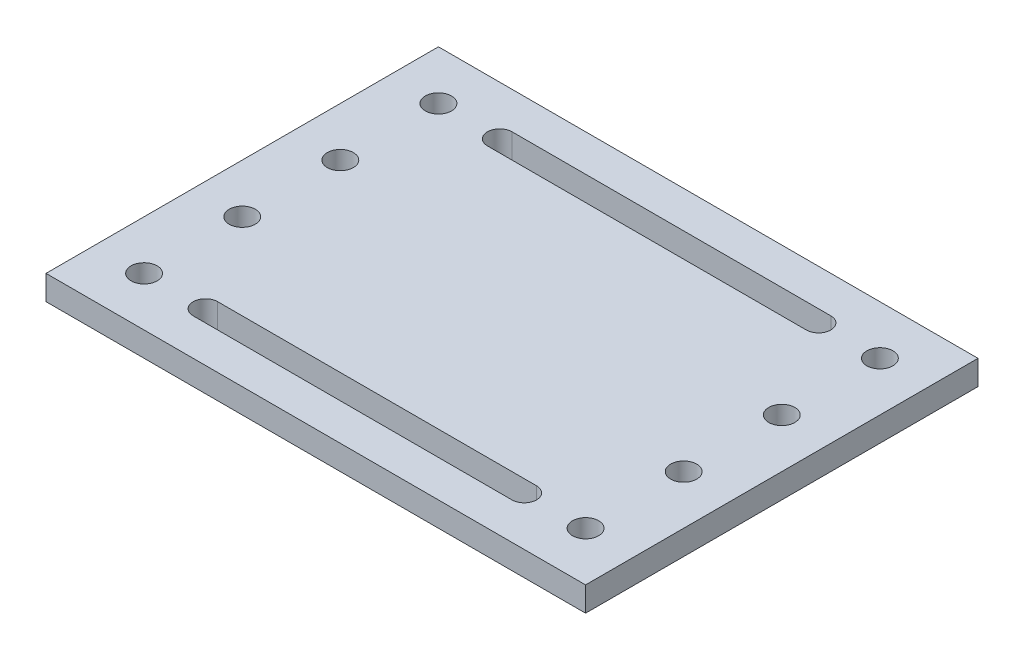
SolidWorks part; units mm, degrees
ref_plane "Front Plane" through (0, 0, 0) normal (0, 0, 1) x (1, 0, 0)
ref_plane "Top Plane" through (0, 0, 0) normal (0, 1, 0) x (1, 0, 0)
ref_plane "Right Plane" through (0, 0, 0) normal (1, 0, 0) x (0, 0, -1)
sketch "Sketch1" plane through (0, 0, 0) normal (0, 1, 0) x (1, 0, 0)
  line L1 (-228.6, -50.8) -> (228.6, -50.8)
  line L2 (-228.6, -50.8) -> (-228.6, 50.8)
  line L3 (-228.6, 50.8) -> (228.6, 50.8)
  line L4 (228.6, -50.8) -> (228.6, 50.8)
  line L5 (-228.6, -50.8) -> (228.6, 50.8) construction
  line L6 (-228.6, 50.8) -> (228.6, -50.8) construction
  point P0 (0, 0)
  dimension "D1" = 457.2
  dimension "D2" = 101.6
extrude "Boss-Extrude1" add sketch "Sketch1" along normal blind 6.35
sketch "Sketch2" plane through (0, 6.35, 0) normal (0, 1, 0) x (1, 0, 0)
  line L0 (200.025, -38.1) -> (117.475, -38.1) construction
  line L1 (200.025, -41.275) -> (117.475, -41.275)
  line L2 (200.025, -34.925) -> (117.475, -34.925)
  line L3 (228.6, -50.8) -> (228.6, 50.8) construction
  line L6 (-228.6, -50.8) -> (228.6, -50.8) construction
  arc A0 (200.025, -41.275) -> (200.025, -34.925) centre (200.025, -38.1) ccw
  arc A1 (117.475, -34.925) -> (117.475, -41.275) centre (117.475, -38.1) ccw
  point P2 (158.75, -38.1)
  dimension "D1" = 82.55
  dimension "D2" = 28.575
  dimension "D3" = 12.7
  dimension "D4" = 6.35
extrude "Cut-Extrude1" cut sketch "Sketch2" against normal through all
mirror "Mirror1" about plane through (0, 0, 0) normal (0, 0, 1) of "Cut-Extrude1"
mirror "Mirror2" [suppressed] about plane through (0, 0, 0) normal (1, 0, 0)
sketch "Sketch3" plane through (0, 6.35, 0) normal (0, 1, 0) x (1, 0, 0)
  line L1 (228.6, 50.8) -> (-228.6, 50.8) construction
  line L2 (-228.6, 50.8) -> (-228.6, -50.8) construction
  point P0 (-215.9, 12.7)
  point P1 (-215.9, 38.1)
  dimension "D1" = 25.4
  dimension "D2" = 12.7
  dimension "D3" = 12.7
hole_wizard "1/4 Clearance Hole1" positions "Sketch4" profile "Sketch5" hole size "1/4" standard "ANSI Inch" end condition through all
sketch "Sketch4" plane through (0, 6.35, 0) normal (0, 1, 0) x (1, 0, 0)
  point P0 (-215.9, 12.7)
  point P3 (-215.9, 38.1)
sketch "Sketch5" plane through (-215.9, 6.35, -12.7) normal (1, 0, 0) x (0, 0, 1)
  line L0 (0, 0) -> (0, 6.35)
  line L1 (0, 6.35) -> (3.3782, 6.35)
  line L2 (3.3782, 6.35) -> (3.3782, 0)
  line L5 (3.3782, 0) -> (0, 0)
  line L11 (0, -6.35) -> (0, 107.95) construction
  dimension "Thru Hole Dia." = 6.7564
  dimension "Thru Hole Depth" = 6.35
mirror "Mirror3" about plane through (0, 0, 0) normal (0, 0, 1) of "1/4 Clearance Hole1"
mirror "Mirror4" about plane through (0, 0, 0) normal (1, 0, 0) of "Mirror3", "1/4 Clearance Hole1"
sketch "Sketch6" plane through (0, 6.35, 0) normal (0, 1, 0) x (1, 0, 0)
  line L0 (-190.5, 38.1) -> (-63.5, 38.1) construction
  line L1 (-190.5, 41.275) -> (-63.5, 41.275)
  line L2 (-190.5, 34.925) -> (-63.5, 34.925)
  line L3 (-228.6, 50.8) -> (-228.6, -50.8) construction
  line L4 (228.6, 50.8) -> (-228.6, 50.8) construction
  arc A0 (-190.5, 41.275) -> (-190.5, 34.925) centre (-190.5, 38.1) ccw
  arc A1 (-63.5, 34.925) -> (-63.5, 41.275) centre (-63.5, 38.1) ccw
  point P2 (-127, 38.1)
  dimension "D1" = 127
  dimension "D2" = 38.1
  dimension "D3" = 12.7
  dimension "D4" = 6.35
extrude "Cut-Extrude2" cut sketch "Sketch6" against normal through all
mirror "Mirror5" about plane through (0, 0, 0) normal (0, 0, 1) of "Cut-Extrude2"
ref_plane "Plane1" through (-190.5, 0, 0) normal (-1, 0, 0) x (0, 0, 1)
ref_plane "Plane2" through (-152.4, 0, 0) normal (-1, 0, 0) x (0, 0, 1)
ref_plane "Plane3" through (200.025, 0, 0) normal (-1, 0, 0) x (0, 0, 1)
ref_plane "Plane4" through (161.925, 0, 0) normal (-1, 0, 0) x (0, 0, 1)
ref_plane "Plane5" through (-63.5, 0, 0) normal (-1, 0, 0) x (0, 0, 1)
ref_plane "Plane6" through (-101.6, 0, 0) normal (-1, 0, 0) x (0, 0, 1)
sketch "Sketch7" plane through (0, 6.35, 0) normal (0, 1, 0) x (1, 0, 0)
  line L0 (228.6, 50.8) -> (-228.6, 50.8) construction
  line L1 (-228.6, -50.8) -> (88.9, -50.8)
  line L2 (-228.6, -50.8) -> (-228.6, 50.8)
  line L3 (-228.6, 50.8) -> (88.9, 50.8)
  line L4 (88.9, -50.8) -> (88.9, 50.8)
  arc A0 (117.475, -34.925) -> (117.475, -41.275) centre (117.475, -38.1) ccw construction
  point P10 (114.3, -38.1)
  dimension "D1" = 25.4
extrude "Cut-Extrude3" cut sketch "Sketch7" against normal through all
sketch "Sketch8" plane through (0, 6.35, 0) normal (0, 1, 0) x (1, 0, 0)
  line L0 (228.6, 50.8) -> (88.9, 50.8) construction
  line L1 (88.9, -50.8) -> (88.9, 50.8) construction
  point P0 (101.6, 38.1)
  point P1 (101.6, 12.7)
  dimension "D1" = 25.4
  dimension "D2" = 12.7
  dimension "D3" = 12.7
hole_wizard "1/4 Clearance Hole2" positions "Sketch9" profile "Sketch10" hole size "1/4" standard "ANSI Inch" end condition through all
sketch "Sketch9" plane through (0, 6.35, 0) normal (0, 1, 0) x (1, 0, 0)
  point P0 (101.6, 38.1)
  point P3 (101.6, 12.7)
sketch "Sketch10" plane through (101.6, 6.35, -38.1) normal (1, 0, 0) x (0, 0, 1)
  line L0 (0, 0) -> (0, 6.35)
  line L1 (0, 6.35) -> (3.3782, 6.35)
  line L2 (3.3782, 6.35) -> (3.3782, 0)
  line L5 (3.3782, 0) -> (0, 0)
  line L11 (0, -6.35) -> (0, 107.95) construction
  dimension "Thru Hole Dia." = 6.7564
  dimension "Thru Hole Depth" = 6.35
mirror "Mirror8" about plane through (0, 0, 0) normal (0, 0, 1) of "1/4 Clearance Hole2"
